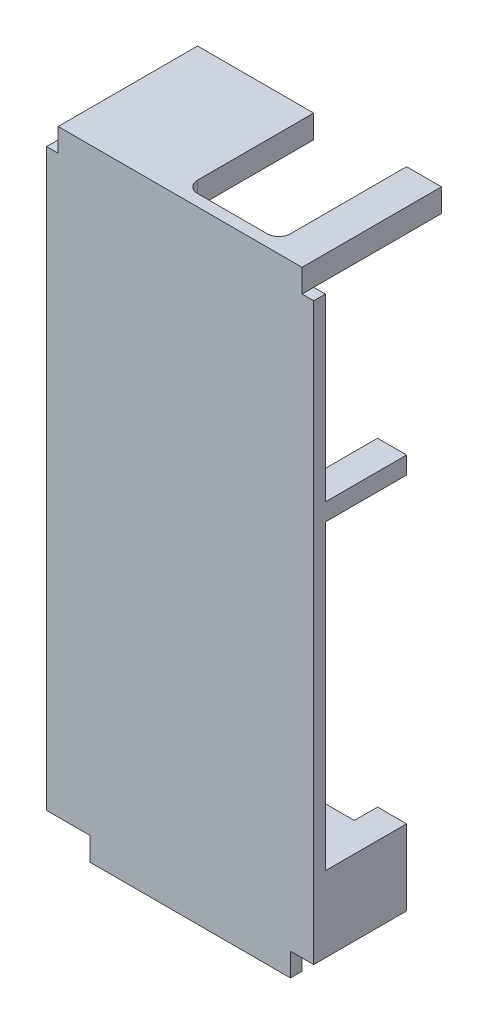
SolidWorks part; units mm, degrees
ref_plane "Front Plane" through (0, 0, 0) normal (0, 0, 1) x (1, 0, 0)
ref_plane "Top Plane" through (0, 0, 0) normal (0, 1, 0) x (1, 0, 0)
ref_plane "Right Plane" through (0, 0, 0) normal (1, 0, 0) x (0, 0, -1)
sketch "Sketch1" plane through (0, 0, 0) normal (0, 0, 1) x (1, 0, 0)
  line L0 (-11.5, -24.7526) -> (11.5, -24.7526)
  line L1 (-11.75, 25.0026) -> (11.75, 25.0026)
  line L2 (-11.75, 25.0026) -> (-11.75, -25.0026)
  line L3 (-11.75, -25.0026) -> (11.75, -25.0026)
  line L4 (11.75, 25.0026) -> (11.75, -25.0026)
  line L5 (11.5, 24.7526) -> (11.5, -24.7526)
  line L6 (-11.5, 24.7526) -> (11.5, 24.7526)
  line L7 (-11.5, 24.7526) -> (-11.5, -24.7526)
  line L8 (0, 26.75) -> (0, -26.75) construction
  line L9 (-10.75, 26.75) -> (10.75, 26.75) construction
  line L10 (-8, -26.75) -> (3, -26.75) construction
  line L11 (0, 26.75) -> (0, 24.7526) construction
  line L12 (-10.5, 26.75) -> (10.5, 26.75)
  line L13 (-10.5, 26.75) -> (-10.5, 24.7526)
  line L14 (-10.5, 24.7526) -> (10.5, 24.7526)
  line L15 (10.5, 26.75) -> (10.5, 24.7526)
  line L16 (-10.75, 25.0026) -> (-10.75, 26.75) construction
  line L17 (9.75, -26.75) -> (3, -26.75) construction
  line L18 (-7.75, -24.7526) -> (9.5, -24.7526)
  line L19 (-7.75, -24.7526) -> (-7.75, -26.75)
  line L20 (-7.75, -26.75) -> (9.5, -26.75)
  line L21 (9.5, -24.7526) -> (9.5, -26.75)
  line L22 (-8, -25.0026) -> (-8, -26.75) construction
  line L23 (9.75, -25.0026) -> (9.75, -26.75) construction
  dimension "D2" = 0.25
  dimension "D3" = 0.25
  dimension "D4" = 0.25
  dimension "D1" = 0.25
extrude "Boss-Extrude1" add sketch "Sketch1" against normal blind 1 contours L15 L12 L13 L1 | L15 L1 L13 L6 | L6 L7 L0 L5 | L21 L0 L19 L3 | L21 L3 L19 L20
sketch "Sketch2" plane through (0, 0, -1) normal (0, 0, -1) x (-1, 0, 0)
  line L0 (-11.5, 24.7526) -> (-11.5, -24.7526) construction
  line L1 (-11.5, -19.7526) -> (11.5, -19.7526)
  line L2 (-11.5, -19.7526) -> (-11.5, -18.2526)
  line L3 (-11.5, -18.2526) -> (11.5, -18.2526)
  line L4 (11.5, -19.7526) -> (11.5, -18.2526)
  line L5 (11.5, 24.7526) -> (11.5, -24.7526) construction
  line L6 (11.5, -24.7526) -> (7.75, -24.7526) construction
  line L7 (11.5, 24.7526) -> (10.5, 24.7526) construction
  line L8 (-11.5, 9.2526) -> (11.5, 9.2526)
  line L9 (-11.5, 9.2526) -> (-11.5, 7.7526)
  line L10 (-11.5, 7.7526) -> (11.5, 7.7526)
  line L11 (11.5, 9.2526) -> (11.5, 7.7526)
  line L12 (0, 9.2526) -> (0, 7.7526) construction
  line L13 (4, 8.5026) -> (-4, 8.5026) construction
  line L14 (-4, 9.2526) -> (4, 9.2526)
  line L15 (-4, 9.2526) -> (-4, 7.7526)
  line L16 (-4, 7.7526) -> (4, 7.7526)
  line L17 (4, 9.2526) -> (4, 7.7526)
  line L18 (0, 8.5026) -> (0, 9.2526) construction
  line L19 (-11.5, -19.0026) -> (11.5, -19.0026) construction
  line L20 (9, 9.2526) -> (-9, 9.2526)
  line L21 (9, 9.2526) -> (9, 7.7526)
  line L22 (9, 7.7526) -> (-9, 7.7526)
  line L23 (-9, 9.2526) -> (-9, 7.7526)
  line L24 (9, 9.2526) -> (-9, 7.7526) construction
  line L25 (9, 7.7526) -> (-9, 9.2526) construction
  line L26 (0, -18.2526) -> (0, -19.7526) construction
  line L28 (9, -18.2526) -> (-9, -18.2526)
  line L29 (9, -18.2526) -> (9, -19.7526)
  line L30 (9, -19.7526) -> (-9, -19.7526)
  line L31 (-9, -18.2526) -> (-9, -19.7526)
  line L32 (9, -18.2526) -> (-9, -19.7526) construction
  line L33 (9, -19.7526) -> (-9, -18.2526) construction
  point P34 (0, -19.0026)
  line M3 (-11.5, 24.7526) -> (-11.5, -24.7526)
  line M9 (11.5, -24.7526) -> (11.5, 24.7526)
  dimension "D1" = 5
  dimension "D2" = 1.5
  dimension "D3" = 15.5
  dimension "D4" = 1.5
  dimension "D5" = 8
  dimension "D6" = 18
extrude "Boss-Extrude2" add sketch "Sketch2" along normal offset from surface (5 mm away) 6 contours L17 L8 L15 L10 | L3 L1 M3 M9 | L23 L8 L10 M3 | L8 L21 L10 M9 | L31 L3 L1 M3 | L3 L29 L1 M9
sketch "Sketch3" plane through (0, 0, -6) normal (0, 0, -1) x (-1, 0, 0)
  line L0 (11.5, -19.7526) -> (-11.5, -19.7526) construction
  line L1 (-11.5, 9.2526) -> (-9, 9.2526)
  line L2 (-11.5, 9.2526) -> (-11.5, 7.7526)
  line L3 (-11.5, 7.7526) -> (-9, 7.7526)
  line L4 (-9, 9.2526) -> (-9, 7.7526)
  line L5 (9, 9.2526) -> (11.5, 9.2526)
  line L6 (9, 9.2526) -> (9, 7.7526)
  line L7 (9, 7.7526) -> (11.5, 7.7526)
  line L8 (11.5, 9.2526) -> (11.5, 7.7526)
  line L9 (-11.5, -18.2526) -> (-9, -18.2526)
  line L10 (-11.5, -18.2526) -> (-11.5, -19.7526)
  line L11 (-11.5, -19.7526) -> (-9, -19.7526)
  line L12 (-9, -18.2526) -> (-9, -19.7526)
  line L14 (11.5, -18.2526) -> (9, -18.2526)
  line L15 (11.5, -18.2526) -> (11.5, -19.7526)
  line L16 (11.5, -19.7526) -> (9, -19.7526)
  line L17 (9, -18.2526) -> (9, -19.7526)
extrude "Boss-Extrude3" add sketch "Sketch3" along normal blind 2
sketch "Sketch4" plane through (0, 0, -1) normal (0, 0, -1) x (-1, 0, 0)
  line L1 (-10.5, 26.75) -> (10.5, 26.75)
  line L2 (-10.5, 26.75) -> (-10.5, 24.7526)
  line L3 (-10.5, 24.7526) -> (10.5, 24.7526)
  line L4 (10.5, 26.75) -> (10.5, 24.7526)
  line L5 (-10.5, 26.75) -> (-7.5, 26.75)
  line L6 (-10.5, 26.75) -> (-10.5, 24.7526)
  line L7 (-10.5, 24.7526) -> (-7.5, 24.7526)
  line L8 (-7.5, 26.75) -> (-7.5, 24.7526)
  line L9 (10.5, 26.75) -> (0.5, 26.75)
  line L10 (10.5, 26.75) -> (10.5, 24.7526)
  line L11 (10.5, 24.7526) -> (0.5, 24.7526)
  line L12 (0.5, 26.75) -> (0.5, 24.7526)
  line M13 (10.5, 24.7526) -> (10.5, 26.75)
  line M14 (10.5, 26.75) -> (-10.5, 26.75)
  line M15 (-10.5, 26.75) -> (-10.5, 24.7526)
  dimension "D1" = 10
  dimension "D2" = 3
extrude "Boss-Extrude4" add sketch "Sketch4" along normal offset from surface (11 mm away) 12 contours L8 L1 L3 M15 | L12 L3 M14 M13 up to face at (0.2917, 0, 0)
sketch "Sketch5" plane through (0, 0, -1) normal (0, 0, -1) x (-1, 0, 0)
  line L0 (-10.5, 26.75) -> (-7.5, 26.75) construction
  line L1 (11.5, 24.7526) -> (7.5, 24.7526)
  line L2 (11.5, 24.7526) -> (11.5, 22.75)
  line L3 (11.5, 22.75) -> (7.5, 22.75)
  line L4 (7.5, 24.7526) -> (7.5, 22.75)
  line L5 (7.75, -26.75) -> (-9.5, -26.75) construction
  line L6 (11.5, -24.7526) -> (8, -24.7526)
  line L7 (11.5, -24.7526) -> (11.5, -21.75)
  line L8 (11.5, -21.75) -> (8, -21.75)
  line L9 (8, -24.7526) -> (8, -21.75)
  line L10 (-9, -19.7526) -> (-9, -18.2526) construction
  line L11 (-11.5, -24.7526) -> (-8, -24.7526)
  line L12 (-11.5, -24.7526) -> (-11.5, -21.75)
  line L13 (-11.5, -21.75) -> (-8, -21.75)
  line L14 (-8, -24.7526) -> (-8, -21.75)
  line L15 (-11.5, -19.7526) -> (-9, -19.7526)
  line L16 (-11.5, -19.7526) -> (-11.5, -21.75)
  line L17 (-11.5, -21.75) -> (-9, -21.75)
  line L18 (-9, -19.7526) -> (-9, -21.75)
  line L19 (9, -18.2526) -> (9, -19.7526) construction
  line L20 (11.5, -19.7526) -> (9, -19.7526)
  line L21 (11.5, -19.7526) -> (11.5, -21.75)
  line L22 (11.5, -21.75) -> (9, -21.75)
  line L23 (9, -19.7526) -> (9, -21.75)
  line M9 (-7.5, 24.7526) -> (-10.5, 24.7526)
  dimension "D1" = 4
  dimension "D2" = 4
  dimension "D3" = 5
  dimension "D4" = 16
extrude "Boss-Extrude5" add sketch "Sketch5" along normal up to surface (7 mm away) contours L11 L14 L13 L12 | L18 L15 L16 L13 | L9 L6 L7 L8 | L20 L23 L8 L21 | L4 L3 L2 M9
fillet "Fillet1" radius 1 6 edges at (-0.5, 25.7513, -1) (7.5, 25.7513, -1) (-4, 8.5026, -1) (-9, 8.5026, -1) (4, 8.5026, -1) (9, 8.5026, -1)
